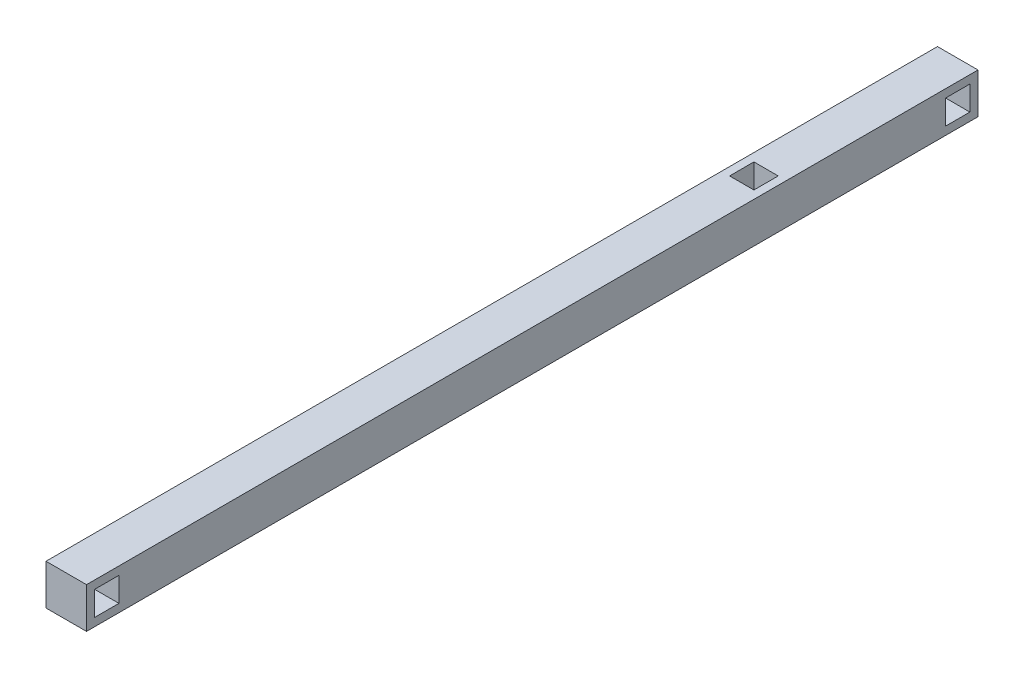
SolidWorks part; units mm, degrees
ref_plane "Front Plane" through (0, 0, 0) normal (0, 0, 1) x (1, 0, 0)
ref_plane "Top Plane" through (0, 0, 0) normal (0, 1, 0) x (1, 0, 0)
ref_plane "Right Plane" through (0, 0, 0) normal (1, 0, 0) x (0, 0, -1)
sketch "Sketch1" plane through (0, 0, 0) normal (0, 0, 1) x (1, 0, 0)
  line L1 (0, 0) -> (5, 0)
  line L2 (0, 0) -> (0, 5)
  line L3 (0, 5) -> (5, 5)
  line L4 (5, 0) -> (5, 5)
  dimension "D1" = 5
  dimension "D2" = 5
extrude "Boss-Extrude1" add sketch "Sketch1" along normal blind 110
sketch "Sketch2" plane through (0, 0, 0) normal (-1, 0, 0) x (0, 0, 1)
  line L0 (0, 5) -> (0, 0) construction
  line L1 (1, 1) -> (4, 1)
  line L2 (1, 1) -> (1, 4)
  line L3 (1, 4) -> (4, 4)
  line L4 (4, 1) -> (4, 4)
  line L5 (110, 5) -> (0, 5) construction
  line L6 (110, 5) -> (110, 0) construction
  line L7 (109, 4) -> (106, 4)
  line L8 (109, 4) -> (109, 1)
  line L9 (109, 1) -> (106, 1)
  line L10 (106, 4) -> (106, 1)
  dimension "D1" = 3
  dimension "D2" = 3
  dimension "D3" = 1
  dimension "D4" = 1
  dimension "D5" = 3
  dimension "D6" = 3
  dimension "D7" = 1
  dimension "D8" = 1
extrude "Cut-Extrude1" cut sketch "Sketch2" against normal blind 9
sketch "Sketch3" plane through (0, 5, 0) normal (0, 1, 0) x (1, 0, 0)
  line L0 (0, -110) -> (0, 0) construction
  line L1 (1, -23.65) -> (4, -23.65)
  line L2 (1, -23.65) -> (1, -26.65)
  line L3 (1, -26.65) -> (4, -26.65)
  line L4 (4, -23.65) -> (4, -26.65)
  line L5 (1, -26.65) -> (4, -23.65) construction
  line L6 (1, -23.65) -> (4, -26.65) construction
  line L7 (5, 0) -> (0, 0) construction
  point P6 (2.5, -25.15)
  dimension "D1" = 3
  dimension "D2" = 3
  dimension "D3" = 1
  dimension "D4" = 4.2426
  dimension "D5" = 4.2426
  dimension "D6" = 25.15
extrude "Cut-Extrude2" cut sketch "Sketch3" against normal blind 9
